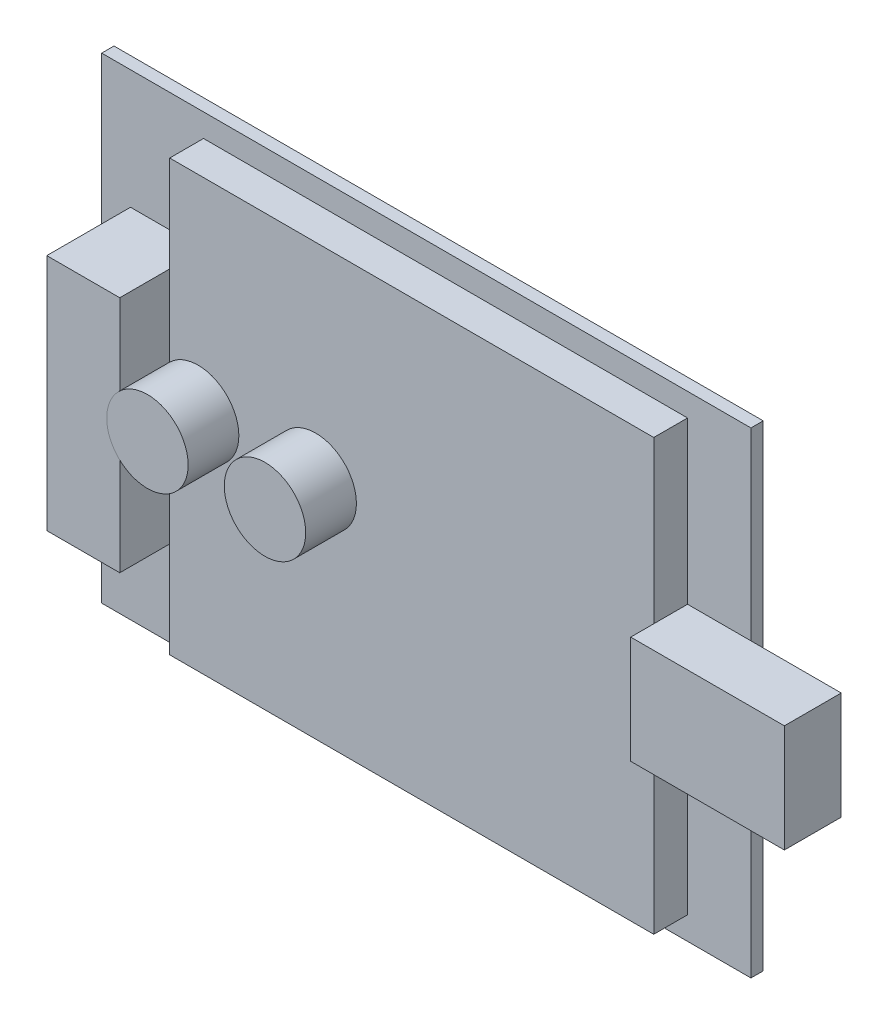
SolidWorks part; units mm, degrees
ref_plane "Front Plane" through (0, 0, 0) normal (0, 0, 1) x (1, 0, 0)
ref_plane "Top Plane" through (0, 0, 0) normal (0, 1, 0) x (1, 0, 0)
ref_plane "Right Plane" through (0, 0, 0) normal (1, 0, 0) x (0, 0, -1)
sketch "Sketch1" plane through (0, 0, 0) normal (0, 0, 1) x (1, 0, 0)
  line L0 (-42.25, -31) -> (42.25, -31)
  line L1 (42.25, -31) -> (42.25, 31)
  line L2 (42.25, 31) -> (-42.25, 31)
  line L3 (-42.25, 31) -> (-42.25, -31)
extrude "PCB" add sketch "Sketch1" along normal blind 1.6
ref_plane "P_Front_1p6" through (0, 0, 1.6) normal (0, 0, 1) x (1, 0, 0)
sketch "Sketch2" plane through (0, 0, 1.6) normal (0, 0, 1) x (1, 0, 0)
  line L0 (-38.5, -15.5) -> (-29, -15.5)
  line L1 (-29, -15.5) -> (-29, 15.5)
  line L2 (-29, 15.5) -> (-38.5, 15.5)
  line L3 (-38.5, 15.5) -> (-38.5, -15.5)
extrude "Terminal_block" add sketch "Sketch2" along normal blind 10.9
ref_plane "P_Front_m2p5" through (0, 0, -2.5) normal (0, 0, 1) x (1, 0, 0)
sketch "Sketch3" plane through (0, 0, -2.5) normal (0, 0, 1) x (1, 0, 0)
  line L0 (-38.5, -15.5) -> (-29, -15.5)
  line L1 (-29, -15.5) -> (-29, 15.5)
  line L2 (-29, 15.5) -> (-38.5, 15.5)
  line L3 (-38.5, 15.5) -> (-38.5, -15.5)
extrude "Terminal_pins" add sketch "Sketch3" along normal blind 2.5
sketch "Sketch4" plane through (0, 0, 1.6) normal (0, 0, 1) x (1, 0, 0)
  line L0 (-29, -28) -> (34, -28)
  line L1 (34, -28) -> (34, 28)
  line L2 (34, 28) -> (-29, 28)
  line L3 (-29, 28) -> (-29, -28)
extrude "Components" add sketch "Sketch4" along normal blind 4.4
sketch "Sketch5" plane through (0, 0, 1.6) normal (0, 0, 1) x (1, 0, 0)
  line L0 (34, -7) -> (54, -7)
  line L1 (54, -7) -> (54, 7)
  line L2 (54, 7) -> (34, 7)
  line L3 (34, 7) -> (34, -7)
extrude "Input_connector" add sketch "Sketch5" along normal blind 7.4
sketch "Sketch6" plane through (0, 0, 1.6) normal (0, 0, 1) x (1, 0, 0)
  circle A0 centre (-25.3, 1.2) radius 5.3
extrude "Cap_1" add sketch "Sketch6" along normal blind 11
sketch "Sketch7" plane through (0, 0, 1.6) normal (0, 0, 1) x (1, 0, 0)
  circle A0 centre (-10, 1.2) radius 5.3
extrude "Cap_2" add sketch "Sketch7" along normal blind 11
